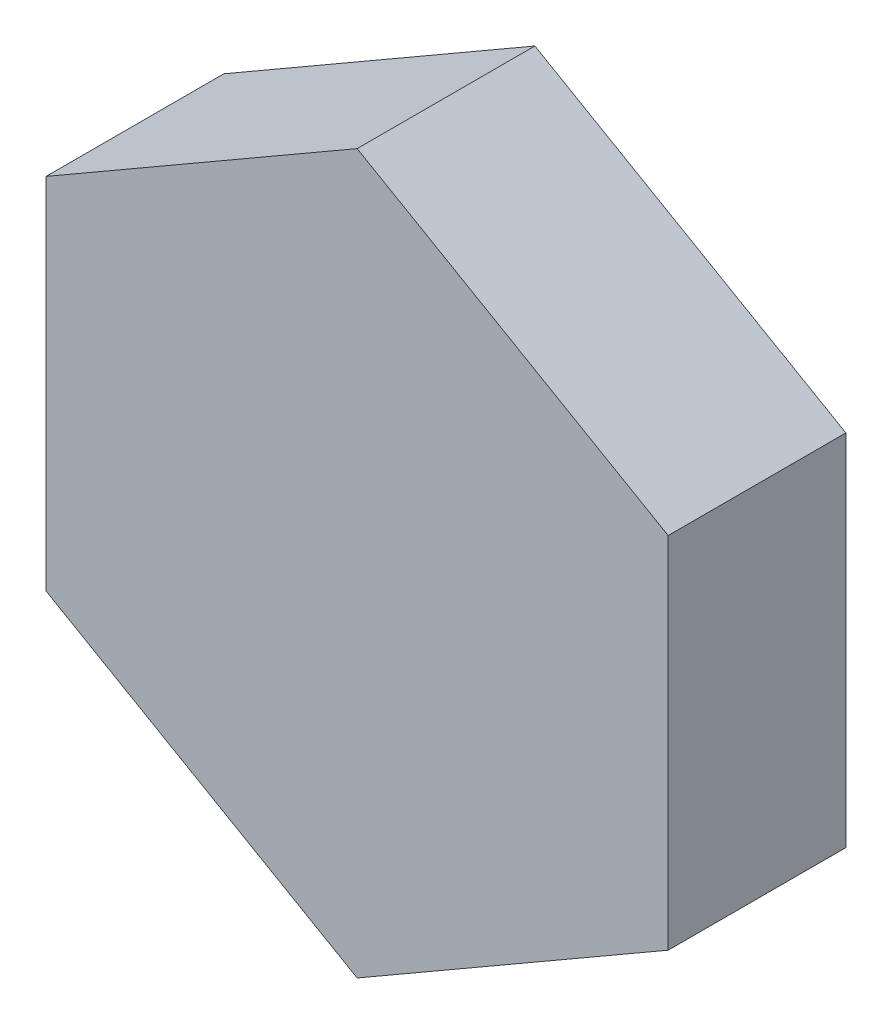
SolidWorks part; units mm, degrees
material "PET"
ref_plane "Front Plane" through (0, 0, 0) normal (0, 0, 1) x (1, 0, 0)
ref_plane "Top Plane" through (0, 0, 0) normal (0, 1, 0) x (1, 0, 0)
ref_plane "Right Plane" through (0, 0, 0) normal (1, 0, 0) x (0, 0, -1)
sketch "Sketch1" plane through (0, 0, 0) normal (0, 0, 1) x (1, 0, 0)
  line L1 (3.5, -2.0207) -> (3.5, 2.0207)
  line L2 (3.5, 2.0207) -> (0, 4.0415)
  line L3 (0, 4.0415) -> (-3.5, 2.0207)
  line L4 (-3.5, 2.0207) -> (-3.5, -2.0207)
  line L5 (-3.5, -2.0207) -> (0, -4.0415)
  line L6 (0, -4.0415) -> (3.5, -2.0207)
  circle A0 centre (0, 0) radius 3.5 construction
  point P1 (0, 0)
  point P10 (3.0339, -2.67)
  dimension "D1" = 7
extrude "Boss-Extrude1" add sketch "Sketch1" along normal blind 2
